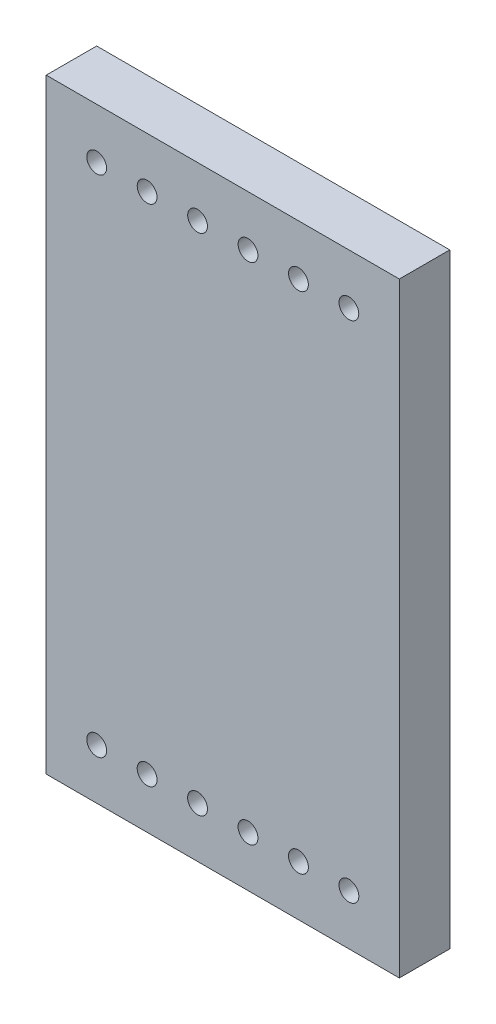
SolidWorks part; units mm, degrees
ref_plane "Front Plane" through (0, 0, 0) normal (0, 0, 1) x (1, 0, 0)
ref_plane "Top Plane" through (0, 0, 0) normal (0, 1, 0) x (1, 0, 0)
ref_plane "Right Plane" through (0, 0, 0) normal (1, 0, 0) x (0, 0, -1)
sketch "Sketch1" plane through (0, 0, 0) normal (0, 0, 1) x (1, 0, 0)
  line L5 (88.9, 1028.7) -> (0, 1028.7)
  line L6 (88.9, 1028.7) -> (88.9, 1181.1)
  line L7 (88.9, 1181.1) -> (0, 1181.1)
  line L8 (0, 1028.7) -> (0, 1181.1)
  circle A4 centre (76.2, 1041.4) radius 2.5
  circle A5 centre (63.5, 1041.4) radius 2.5
  circle A6 centre (50.8, 1041.4) radius 2.5
  circle A7 centre (76.2, 1168.4) radius 2.4892
  circle A8 centre (63.5, 1168.4) radius 2.4892
  circle A9 centre (50.8, 1168.4) radius 2.4892
  circle A10 centre (38.1, 1168.4) radius 2.4892
  circle A11 centre (38.1, 1041.4) radius 2.5
  circle A12 centre (25.4, 1168.4) radius 2.4892
  circle A13 centre (25.4, 1041.4) radius 2.5
  circle A14 centre (12.7, 1168.4) radius 2.4892
  circle A15 centre (12.7, 1041.4) radius 2.5
  point P7 (-12.7, 1028.7)
  dimension "D3" = 4.9784
  dimension "D1" = 4.9784
  dimension "D2" = 4.9784
  dimension "D4" = 12.7
  dimension "D5" = 12.7
  dimension "D6" = 12.7
  dimension "D7" = 12.7
  dimension "D8" = 12.7
  dimension "D9" = 12.7
  dimension "D10" = 4
extrude "Boss-Extrude1" add sketch "Sketch1" along normal blind 12.7
